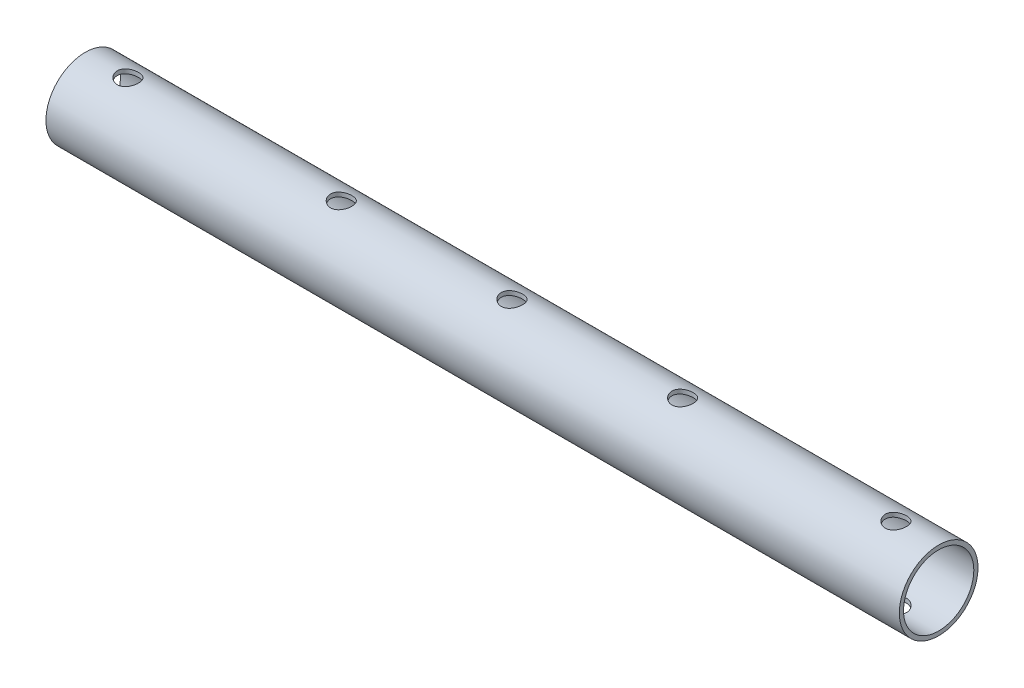
SolidWorks part; units mm, degrees
material "Galvanized Steel"
ref_plane "Front Plane" through (0, 0, 0) normal (0, 0, 1) x (1, 0, 0)
ref_plane "Top Plane" through (0, 0, 0) normal (0, 1, 0) x (1, 0, 0)
ref_plane "Right Plane" through (0, 0, 0) normal (1, 0, 0) x (0, 0, -1)
sketch "Sketch3" plane through (0, 0, 0) normal (1, 0, 0) x (0, 0, -1)
  circle A0 centre (0, 0) radius 10.4648
  circle A1 centre (0, 0) radius 11.7094
  dimension "D1" = 20.9296
  dimension "D2" = 23.4188
extrude "Boss-Extrude1" add sketch "Sketch3" along normal blind 254
sketch "Sketch4" plane through (0, 0, 0) normal (0, 1, 0) x (1, 0, 0)
  line L0 (254, -11.7094) -> (254, 11.7094) construction
  line L1 (0, 11.7094) -> (0, -11.7094) construction
  circle A0 centre (127, 0) radius 3.175
  circle A1 centre (12.7, 0) radius 3.175
  circle A2 centre (76.2, 0) radius 3.175
  circle A3 centre (177.8, 0) radius 3.175
  circle A4 centre (241.3, 0) radius 3.175
  dimension "D1" = 6.35
  dimension "D2" = 6.35
  dimension "D3" = 6.35
  dimension "D4" = 6.35
  dimension "D5" = 6.35
  dimension "D6" = 127
  dimension "D7" = 12.7
  dimension "D8" = 12.7
  dimension "D9" = 63.5
  dimension "D10" = 63.5
extrude "Cut-Extrude1" cut sketch "Sketch4" along normal through all and the other way through all
